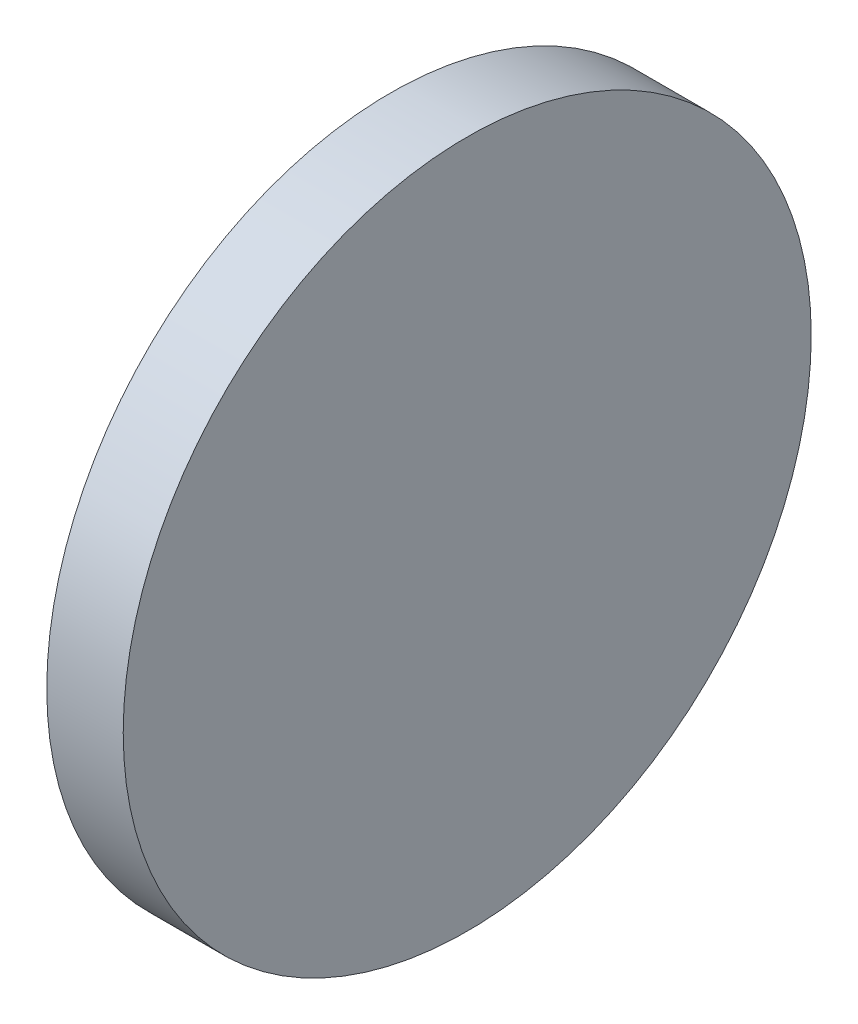
SolidWorks part; units mm, degrees
ref_plane "Front Plane" through (0, 0, 0) normal (0, 0, 1) x (1, 0, 0)
ref_plane "Top Plane" through (0, 0, 0) normal (0, 1, 0) x (1, 0, 0)
ref_plane "Right Plane" through (0, 0, 0) normal (1, 0, 0) x (0, 0, -1)
sketch "Sketch1" plane through (0, 0, 0) normal (1, 0, 0) x (0, 0, -1)
  circle A0 centre (0, 0) radius 22.5
  dimension "D1" = 45
extrude "Boss-Extrude1" add sketch "Sketch1" along normal blind 5 contours A0
